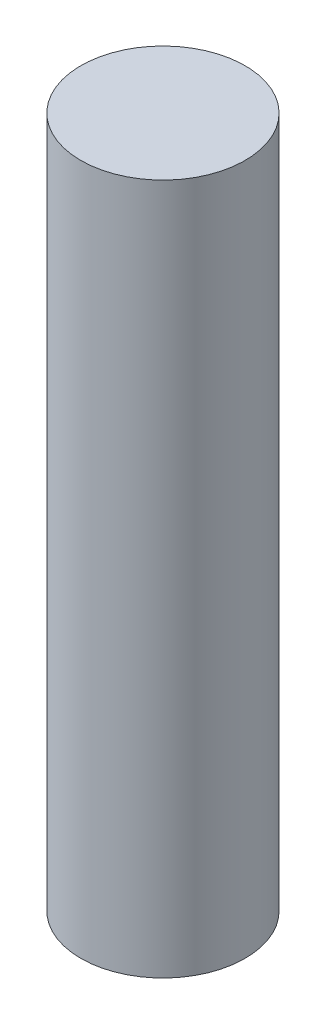
SolidWorks part; units mm, degrees
other "Markup1"
sketch "Sketch2" plane through (2.1304, 33.655, 0.8274) normal (0.0452, 0.999, 0.0024) x (0.2207, -0.0077, -0.9753)
material "6061 Alloy"
ref_plane "Front Plane" through (0, 0, 0) normal (0, 0, 1) x (1, 0, 0)
ref_plane "Top Plane" through (0, 0, 0) normal (0, 1, 0) x (1, 0, 0)
ref_plane "Right Plane" through (0, 0, 0) normal (1, 0, 0) x (0, 0, -1)
sketch "Sketch1" plane through (0, 0, 0) normal (0, 1, 0) x (1, 0, 0)
  circle A0 centre (-1.8696, 3.1726) radius 4
  dimension "D1" = 8
extrude "Boss-Extrude1" add sketch "Sketch1" along normal blind 33.655
